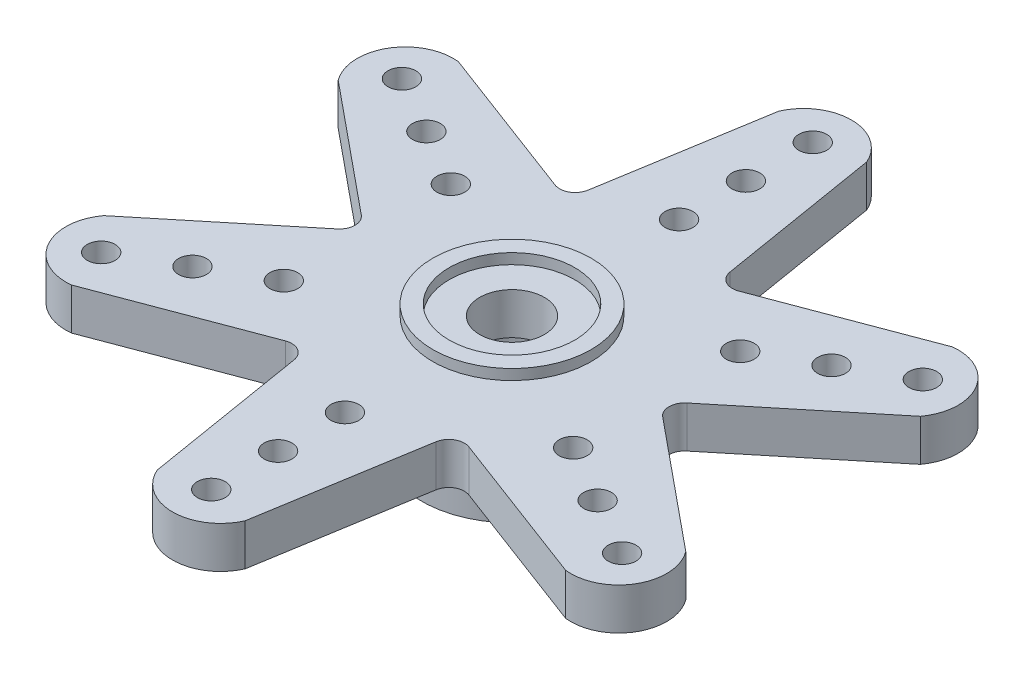
SolidWorks part; units mm, degrees
material "Nylon 6/10"
ref_plane "Front Plane" through (0, 0, 0) normal (0, 0, 1) x (1, 0, 0)
ref_plane "Top Plane" through (0, 0, 0) normal (0, 1, 0) x (1, 0, 0)
ref_plane "Right Plane" through (0, 0, 0) normal (1, 0, 0) x (0, 0, -1)
sketch "Sketch1" plane through (0, 0, 0) normal (0, 1, 0) x (1, 0, 0)
  circle A0 centre (0, 0) radius 4.064
  circle A1 centre (0, 0) radius 2.794
  dimension "D1" = 8.128
  dimension "D2" = 5.588
extrude "Boss-Extrude1" add sketch "Sketch1" along normal blind 3.302
sketch "Sketch2" plane through (0, 3.302, 0) normal (0, 1, 0) x (1, 0, 0)
  line L0 (0, 0) -> (0, -7.5005) construction
  line L3 (0, 0) -> (3.1844, 6.5981) construction
  line L4 (0, 0) -> (4.1219, 6.0568) construction
  line L5 (0, 0) -> (0, 15.24) construction
  line L6 (0, -7.5005) -> (0, -10.5005) construction
  line L7 (0, -10.5005) -> (0, -13.5005) construction
  line L15 (3.1844, 6.5981) -> (1.9734, 13.9505)
  line L16 (-3.1844, 6.5981) -> (-1.9734, 13.9505)
  line L17 (4.1219, 6.0568) -> (11.0948, 8.6843)
  line L18 (7.3063, 0.5413) -> (13.0682, 5.2662)
  line L19 (7.3063, -0.5413) -> (13.0682, -5.2662)
  line L20 (4.1219, -6.0568) -> (11.0948, -8.6843)
  line L21 (3.1844, -6.5981) -> (1.9734, -13.9505)
  line L22 (-3.1844, -6.5981) -> (-1.9734, -13.9505)
  line L23 (-4.1219, -6.0568) -> (-11.0948, -8.6843)
  line L24 (-7.3063, -0.5413) -> (-13.0682, -5.2662)
  line L25 (-7.3063, 0.5413) -> (-13.0682, 5.2662)
  line L26 (-4.1219, 6.0568) -> (-11.0948, 8.6843)
  line L31 (0.002, 0) -> (-3.1824, -6.5981) construction
  line L32 (0.002, 0) -> (-4.1199, -6.0568) construction
  line L33 (0.0015, -0.0009) -> (-7.3048, -0.5421) construction
  line L34 (0.0015, -0.0009) -> (-7.3048, 0.5404) construction
  line L35 (0.0005, -0.0009) -> (-4.1214, 6.056) construction
  line L36 (0.0005, -0.0009) -> (-3.1839, 6.5972) construction
  line L37 (0.0015, 0.0009) -> (4.1234, -6.056) construction
  line L38 (0.0015, 0.0009) -> (3.1859, -6.5972) construction
  line L39 (0.0005, 0.0009) -> (7.3068, 0.5421) construction
  line L40 (0.0005, 0.0009) -> (7.3068, -0.5404) construction
  arc A0 (-1.9734, 13.9505) -> (1.9734, 13.9505) centre (0, 13.0852) cw
  arc A1 (11.0948, 8.6843) -> (13.0682, 5.2662) centre (11.3321, 6.5426) cw
  arc A2 (13.0682, -5.2662) -> (11.0948, -8.6843) centre (11.3321, -6.5426) cw
  arc A3 (1.9734, -13.9505) -> (-1.9734, -13.9505) centre (0, -13.0852) cw
  arc A4 (-11.0948, -8.6843) -> (-13.0682, -5.2662) centre (-11.3321, -6.5426) cw
  arc A5 (-13.0682, 5.2662) -> (-11.0948, 8.6843) centre (-11.3321, 6.5426) cw
  arc A6 (3.1844, 6.5981) -> (4.1219, 6.0568) centre (3.8751, 6.7119) ccw
  arc A7 (7.3063, 0.5413) -> (7.3063, -0.5413) centre (7.7502, 0) ccw
  arc A8 (4.1219, -6.0568) -> (3.1844, -6.5981) centre (3.8751, -6.7119) ccw
  arc A9 (-3.1844, -6.5981) -> (-4.1219, -6.0568) centre (-3.8751, -6.7119) ccw
  arc A10 (-7.3063, -0.5413) -> (-7.3063, 0.5413) centre (-7.7502, 0) ccw
  arc A11 (-4.1219, 6.0568) -> (-3.1844, 6.5981) centre (-3.8751, 6.7119) ccw
  circle A12 centre (0, -7.5005) radius 0.625
  circle A13 centre (0, -10.5005) radius 0.625
  circle A14 centre (0, -13.5005) radius 0.625
  circle A15 centre (-11.6917, -6.7502) radius 0.625
  circle A16 centre (-9.0937, -5.2502) radius 0.625
  circle A17 centre (-6.4956, -3.7502) radius 0.625
  circle A18 centre (-11.6917, 6.7502) radius 0.625
  circle A19 centre (-9.0937, 5.2502) radius 0.625
  circle A20 centre (-6.4956, 3.7502) radius 0.625
  circle A21 centre (0, 13.5005) radius 0.625
  circle A22 centre (0, 10.5005) radius 0.625
  circle A23 centre (0, 7.5005) radius 0.625
  circle A24 centre (11.6917, 6.7502) radius 0.625
  circle A25 centre (9.0937, 5.2502) radius 0.625
  circle A26 centre (6.4956, 3.7502) radius 0.625
  circle A27 centre (11.6917, -6.7502) radius 0.625
  circle A28 centre (9.0937, -5.2502) radius 0.625
  circle A29 centre (6.4956, -3.7502) radius 0.625
  point P4 (0, 0)
  point P12 (0, 0)
  point P16 (0.0005, 0.0009)
  point P20 (0.0015, 0.0009)
  point P24 (0.002, 0)
  point P28 (0.0015, -0.0009)
  point P32 (0.0005, -0.0009)
  point P35 (0.001, 0)
  point P38 (0, 15.24)
  point P59 (0, 0)
  point P76 (0, 0)
  point P83 (0, 0)
  point P110 (0, 0)
  dimension "D5" = 6
  dimension "D2" = 7.5005
  dimension "D3" = 7.3263
  dimension "D4" = 8.474
  dimension "D7" = 7.4515
  dimension "D8" = 144.884
  dimension "D12" = 3
  dimension "D13" = 3
  dimension "D6" = 6
  dimension "D9" = 6
  dimension "D10" = 6
  dimension "D11" = 6
extrude "Boss-Extrude2" add sketch "Sketch2" along normal blind 1.87
sketch "Sketch4" plane through (0, 5.172, 0) normal (0, 1, 0) x (1, 0, 0)
  circle A0 centre (0, 0) radius 1.45
extrude "Cut-Extrude1" cut sketch "Sketch4" against normal through all
sketch "Sketch5" plane through (0, 5.172, 0) normal (0, 1, 0) x (1, 0, 0)
  circle A0 centre (0, 0) radius 2.82
  circle A2 centre (0, 0) radius 3.555
  dimension "D1" = 5.64
  dimension "D2" = 7.11
extrude "Boss-Extrude3" add sketch "Sketch5" along normal blind 0.47
